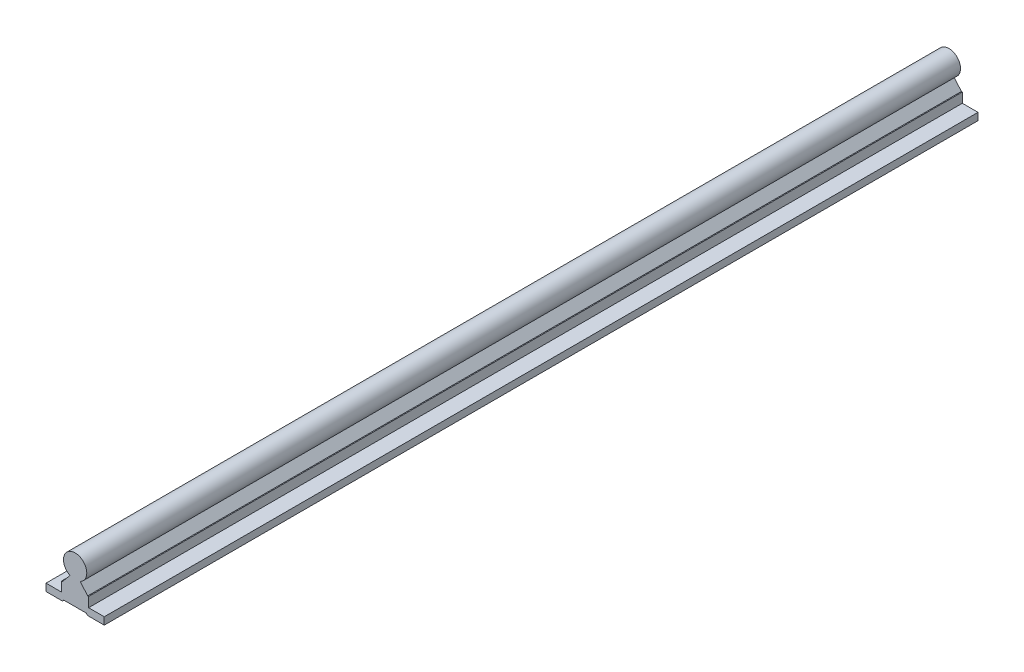
SolidWorks part; units mm, degrees
material "1.0037 (S235JR)"
ref_plane "Płaszczyzna przednia" through (0, 0, 0) normal (0, 0, 1) x (1, 0, 0)
ref_plane "Płaszczyzna górna" through (0, 0, 0) normal (0, 1, 0) x (1, 0, 0)
ref_plane "Płaszczyzna prawa" through (0, 0, 0) normal (1, 0, 0) x (0, 0, -1)
sketch "Szkic1" plane through (0, 0, 0) normal (0, 0, 1) x (1, 0, 0)
  line L0 (0, 0) -> (0, 33) construction
  line L1 (-3.4871, 17.8) -> (-8.6056, 11.7)
  line L2 (-8.6056, 11.7) -> (-9.25, 11.7)
  line L3 (-9.25, 11.7) -> (-9.25, 5)
  line L4 (-9.25, 5) -> (-20, 5)
  line L5 (-20, 5) -> (-20, 0)
  line L6 (-20, 0) -> (-8.6056, 0)
  line L7 (-8.6056, 0) -> (-7.7665, 1)
  line L8 (-7.7665, 1) -> (7.7665, 1)
  line L9 (8.6056, 0) -> (7.7665, 1)
  line L10 (20, 0) -> (8.6056, 0)
  line L11 (20, 5) -> (20, 0)
  line L12 (9.25, 5) -> (20, 5)
  line L13 (9.25, 11.7) -> (9.25, 5)
  line L14 (8.6056, 11.7) -> (9.25, 11.7)
  line L15 (3.4871, 17.8) -> (8.6056, 11.7)
  arc A0 (3.4871, 17.8) -> (-3.4871, 17.8) centre (0, 25) ccw
  point P15 (0, 1)
  dimension "D1" = 1
  dimension "D" = 16
  dimension "W" = 40
  dimension "J" = 18.5
  dimension "O" = 80
  dimension "T" = 5
  dimension "K" = 11.7
  dimension "F" = 17.8
  dimension "H" = 25
extrude "Dodanie-wyciągnięcie1" add sketch "Szkic1" along normal blind 600
sketch "Szkic2" plane through (0, 0, 0) normal (0, -1, 0) x (1, 0, 0)
  line L0 (0, 0) -> (0, 600) construction
  line L1 (-7.7665, 600) -> (7.7665, 600) construction
